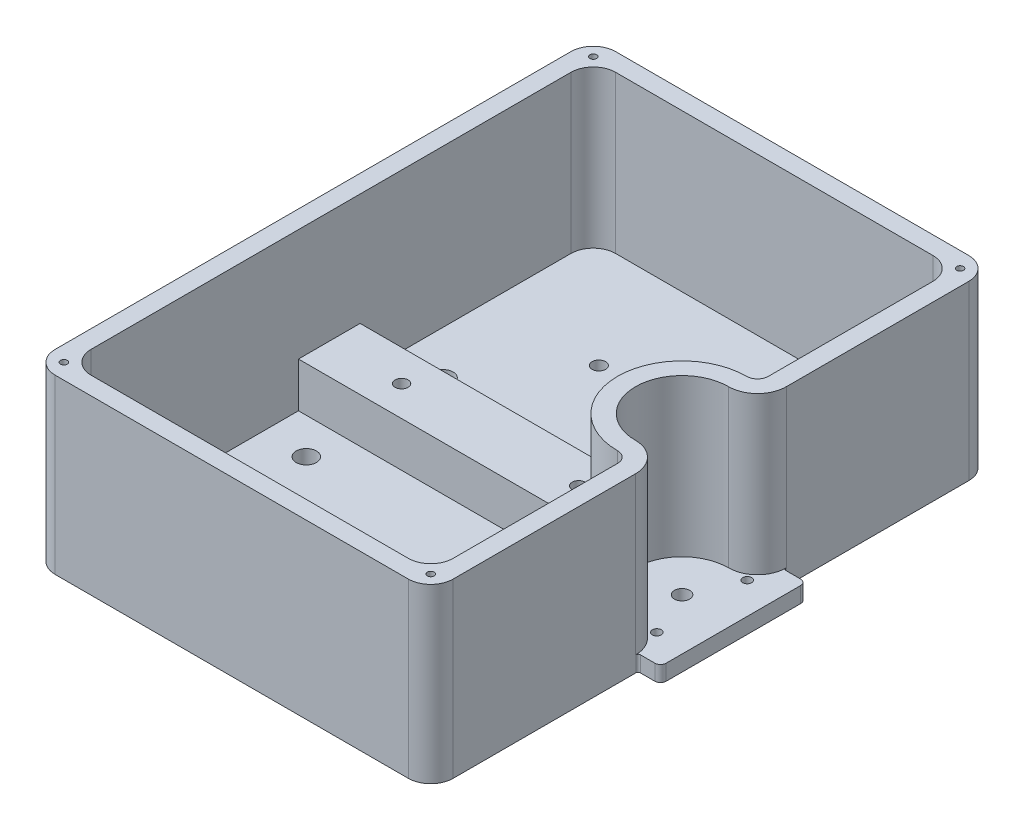
SolidWorks part; units mm, degrees
ref_plane "Alzado" through (0, 0, 0) normal (0, 0, 1) x (1, 0, 0)
ref_plane "Planta" through (0, 0, 0) normal (0, 1, 0) x (1, 0, 0)
ref_plane "Vista lateral" through (0, 0, 0) normal (1, 0, 0) x (0, 0, -1)
sketch "Croquis1" plane through (0, 4, 0) normal (0, 1, 0) x (1, 0, 0)
  line L0 (-20, -125) -> (157.5, -125)
  line L1 (-20, -125) -> (-20, 125)
  line L2 (157.5, -125) -> (157.5, 125)
  line L3 (-20, 125) -> (157.5, 125)
  line L4 (-20, -125) -> (157.5, 125) construction
  line L5 (157.5, -125) -> (-20, 125) construction
  line L9 (0, 35.5) -> (0, -35.5) construction
  circle A1 centre (153.5, -20.15) radius 2 construction
  circle A2 centre (144.6, 0) radius 3.4 construction
  circle A3 centre (153.5, 20.15) radius 2 construction
  circle A4 centre (37.5, 70) radius 3 construction
  circle A7 centre (37.5, -70) radius 3 construction
  circle A8 centre (153.5, -20.15) radius 2
  circle A9 centre (144.6, 0) radius 3.4
  circle A10 centre (153.5, 20.15) radius 2
  circle A11 centre (37.5, 70) radius 3
  circle A14 centre (37.5, -70) radius 3
  circle A15 centre (7.5, -30.5) radius 4.5 construction
  circle A16 centre (7.5, 30.5) radius 4.5 construction
  circle A17 centre (7.5, -30.5) radius 4.5
  circle A18 centre (7.5, 30.5) radius 4.5
  point P1 (68.75, 0)
  dimension "D1" = 177.5
  dimension "D2" = 250
  dimension "D3" = 20
extrude "Saliente-Extruir1" add sketch "Croquis1" along normal blind 7
sketch "Croquis3" plane through (0, 11, 0) normal (0, 1, 0) x (1, 0, 0)
  line L0 (149.5, 117) -> (-12, 117)
  line L1 (-12, 117) -> (-12, -117)
  line L2 (-12, -117) -> (149.5, -117)
  line L3 (149.5, 125) -> (149.5, -125) construction
  line L4 (-20, 125) -> (-20, -125)
  line L5 (-20, -125) -> (157.5, -125)
  line L6 (157.5, -125) -> (157.5, 125)
  line L7 (157.5, 125) -> (-20, 125)
  line L8 (-20, 125) -> (-20, -125)
  line L9 (-20, -125) -> (157.5, -125)
  line L11 (157.5, 125) -> (-20, 125)
  line L13 (157.5, 117) -> (-12, 117) construction
  line L14 (-12, -117) -> (157.5, -117) construction
  line L15 (157.5, 125) -> (157.5, 33.65)
  line L17 (157.5, -33.65) -> (157.5, -125)
  line L20 (149.5, -33.65) -> (149.5, -117)
  line L22 (149.5, 117) -> (149.5, 33.65)
  arc A0 (157.5, 33.65) -> (144.6, 20.75) centre (144.6, 33.65) cw
  circle A2 centre (144.6, 0) radius 20.75
  arc A3 (144.6, 20.75) -> (144.6, -20.75) centre (144.6, 0) ccw
  arc A5 (144.6, 28.75) -> (144.6, -28.75) centre (144.6, 0) ccw
  circle A9 centre (144.6, 0) radius 20.75 construction
  circle A10 centre (144.6, 0) radius 28.75 construction
  arc A13 (149.5, 33.65) -> (144.6, 28.75) centre (144.6, 33.65) cw
  arc A14 (157.5, -33.65) -> (144.6, -20.75) centre (144.6, -33.65) ccw
  arc A16 (149.5, -33.65) -> (144.6, -28.75) centre (144.6, -33.65) ccw
  point P20 (171.85, 0)
  point P38 (165.8778, 6.5053)
  dimension "D3" = 8
  dimension "D1" = 0
  dimension "D2" = 8
  dimension "D4" = 1
  dimension "D7" = 8
extrude "Saliente-Extruir2" add sketch "Croquis3" along normal blind 70
fillet "Redondeo1" radius 10 8 edges at (-20, 42.5, 125) (-20, 42.5, -125) (157.5, 42.5, -125) (157.5, 42.5, 125) (-12, 46, 117) (149.5, 46, -117) (-12, 46, -117) (149.5, 46, 117)
sketch "Croquis4" plane through (0, 11, 0) normal (0, 1, 0) x (1, 0, 0)
  line L0 (157.5, 32.5) -> (157.5, -32.5)
  line L1 (157.5, 32.5) -> (167.5, 32.5)
  line L2 (157.5, -32.5) -> (167.5, -32.5)
  line L3 (167.5, 32.5) -> (167.5, -32.5)
  line L4 (157.5, 32.5) -> (167.5, -32.5) construction
  line L5 (157.5, -32.5) -> (167.5, 32.5) construction
  line L6 (149.5, -32.5) -> (229.25, -32.5) construction
  line L7 (229.25, 32.5) -> (149.5, 32.5) construction
  line L8 (157.5, -33.65) -> (157.5, 33.65) construction
  point P1 (162.5, 0)
  dimension "D1" = 10
extrude "Saliente-Extruir3" add sketch "Croquis4" against normal blind 7
fillet "Redondeo3" radius 1 2 edges at (157.5, 7.5, -32.5) (157.5, 7.5, 32.5)
fillet "Redondeo4" radius 2.5 2 edges at (167.5, 7.5, 32.5) (167.5, 7.5, -32.5)
sketch "Croquis5" plane through (0, 11, 0) normal (0, 1, 0) x (1, 0, 0)
  line L0 (-12, 107) -> (-12, -107) construction
  line L1 (-12, -14.5) -> (109, -14.5)
  line L2 (-12, -14.5) -> (-12, 13)
  line L3 (-12, 13) -> (109, 13)
  line L4 (109, -14.5) -> (109, 13)
  line L5 (1.3295, -84.5) -> (104.6759, -84.5) construction
  line L6 (-12, -107) -> (109, -107)
  line L7 (-12, -107) -> (-12, -79.5)
  line L8 (-12, -79.5) -> (109, -79.5)
  line L9 (109, -107) -> (109, -79.5)
  line L10 (108, -102) -> (-2, -102) construction
  line L11 (108, -68.5) -> (108, -102) construction
  line L12 (104.6759, -9.5) -> (28.7457, -9.5) construction
  line L13 (-2, 8) -> (108, 8) construction
  line L14 (108, 8) -> (108, -25.5) construction
  dimension "D1" = 5
  dimension "D2" = 5
  dimension "D3" = 1
  dimension "D4" = 5
  dimension "D5" = 5
  dimension "D6" = 1
extrude "Saliente-Extruir4" add sketch "Croquis5" along normal blind 20
sketch "Croquis7" plane through (0, 4, 0) normal (0, -1, 0) x (1, 0, 0)
  circle A0 centre (99.5, 1) radius 3
  circle A1 centre (20.5, 1) radius 3
  circle A2 centre (99.5, 93) radius 3
  circle A3 centre (20.5, 93) radius 3
  dimension "D1" = 6
hole_wizard "Avellanado para tornillo con cabeza ovalada de #121" positions "Croquis12" profile "Croquis14" countersink size "#12" standard "Ansi Inch" end condition through all
sketch "Croquis12" plane through (0, 4, 0) normal (0, -1, 0) x (-1, 0, 0)
  point P0 (-99.5, -93)
  point P3 (-20.5, -93)
  point P6 (-20.5, -1)
  point P9 (-99.5, -1)
sketch "Croquis14" plane through (99.5, 4, 93) normal (1, 0, 0) x (0, 0, -1)
  line L0 (0, 0) -> (0, 77)
  line L1 (0, 77) -> (2.8956, 77)
  line L2 (2.8956, 77) -> (2.8956, 3.068)
  line L3 (2.8956, 3.068) -> (5.5626, 0)
  line L5 (5.5626, 0) -> (0, 0)
  line L6 (-2.8956, 3.068) -> (-5.5626, 0) construction
  line L11 (0, -6.35) -> (0, 107.95) construction
  dimension "Diámetro de taladro hasta el siguiente" = 5.7912
  dimension "Profundidad de taladro hasta el siguiente" = 77
  dimension "Diámetro de avellanado cercano" = 11.1252
  dimension "Ángulo de avellanado cercano" = 82
sketch "Croquis15" plane through (0, 81, 0) normal (0, 1, 0) x (1, 0, 0)
  line L0 (154.5711, -122.0711) -> (146.5711, -114.0711) construction
  line L1 (-17.0711, -122.0711) -> (-9.0711, -114.0711) construction
  line L2 (-42.35, 0) -> (42.35, 0) construction
  arc A1 (139.5, -117) -> (149.5, -107) centre (139.5, -107) ccw construction
  arc A3 (147.5, -125) -> (157.5, -115) centre (147.5, -115) ccw construction
  circle A5 centre (150.5711, -118.0711) radius 1.5
  arc A7 (-20, -115) -> (-10, -125) centre (-10, -115) ccw construction
  arc A8 (-12, -107) -> (-2, -117) centre (-2, -107) ccw construction
  circle A9 centre (-13.0711, -118.0711) radius 1.5
  circle A10 centre (-13.0711, 118.0711) radius 1.5
  circle A11 centre (150.5711, 118.0711) radius 1.5
  dimension "D2" = 3
  dimension "D1" = 3
extrude "Cortar-Extruir1" cut sketch "Croquis15" against normal blind 5
